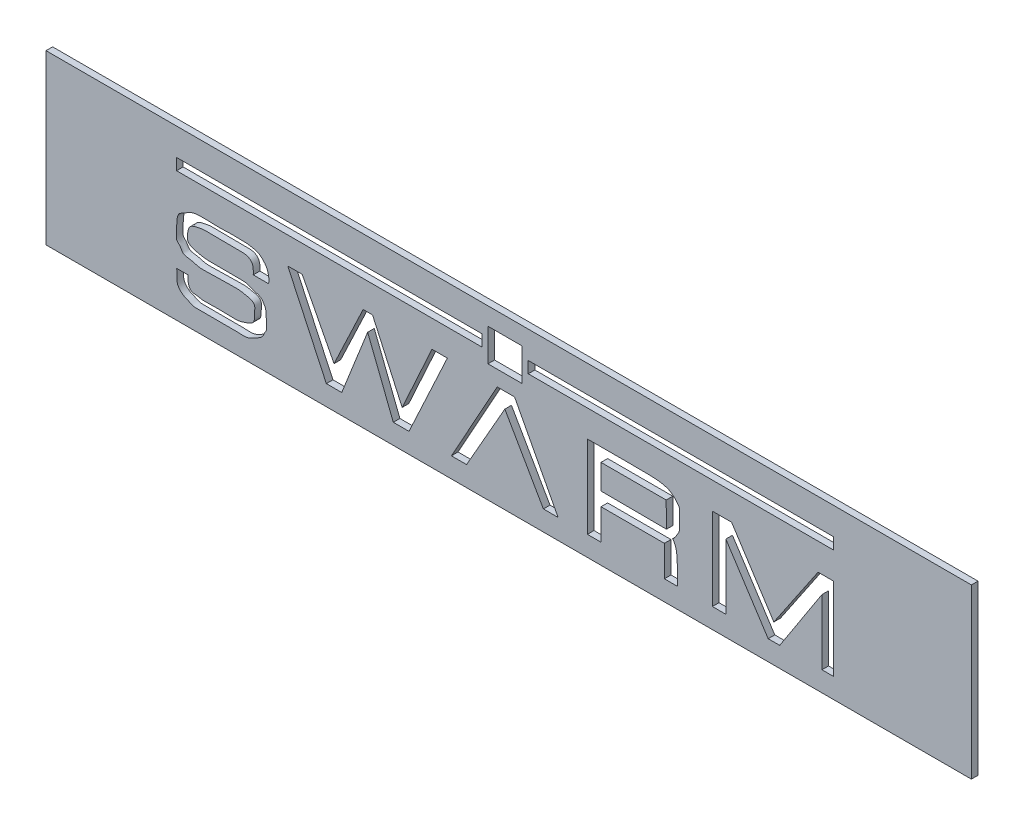
SolidWorks part; units mm, degrees
ref_plane "Front Plane" through (0, 0, 0) normal (0, 0, 1) x (1, 0, 0)
ref_plane "Top Plane" through (0, 0, 0) normal (0, 1, 0) x (1, 0, 0)
ref_plane "Right Plane" through (0, 0, 0) normal (1, 0, 0) x (0, 0, -1)
sketch "Sketch1" plane through (0, 0, 0) normal (0, 0, 1) x (1, 0, 0)
  line L1 (-222.25, -40.4) -> (222.25, -40.4)
  line L2 (-222.25, -40.4) -> (-222.25, 40.4)
  line L3 (-222.25, 40.4) -> (222.25, 40.4)
  line L4 (222.25, -40.4) -> (222.25, 40.4)
  line L5 (-222.25, -40.4) -> (222.25, 40.4) construction
  line L6 (-222.25, 40.4) -> (222.25, -40.4) construction
  point P0 (0, 0)
  dimension "D1" = 80.8
  dimension "D2" = 444.5
sketch "Sketch2" plane through (0, 0, 0) normal (0, 0, 1) x (1, 0, 0)
  line L0 (-115.5, 3.8386) -> (141.8333, 3.8386) construction
  line L1 (148.6027, 8.8845) -> (155.9618, 8.8845)
  line L2 (-222.25, -40.4) -> (222.25, 40.4) construction
  line L3 (-122.7062, -3.1004) -> (-115.2991, -3.1004)
  line L4 (-159.538, -18.7768) -> (-153.9559, -18.7768)
  line L11 (-106.1193, 8.8868) -> (-99.1852, 8.8868)
  line L12 (-99.1852, 8.8868) -> (-83.8919, -20.6337)
  line L13 (-83.8919, -20.6337) -> (-69.9228, 8.8868)
  line L14 (-51.166, -22.4751) -> (-36.8436, 8.8868)
  line L15 (-36.8436, 8.8868) -> (-29.4635, 8.8868)
  line L16 (-29.4635, 8.8868) -> (-47.8873, -30.7813)
  line L17 (-47.8873, -30.7813) -> (-55.4212, -30.7813)
  line L18 (-55.4212, -30.7813) -> (-67.7538, 0.5106)
  line L19 (-67.7538, 0.5106) -> (-80.2018, -30.7813)
  line L20 (-80.2018, -30.7813) -> (-87.5964, -30.7813)
  line L21 (-87.5964, -30.7813) -> (-106.1193, 8.8868)
  line L22 (-5.5054, 8.8868) -> (2.8245, 8.8868)
  line L23 (2.8245, 8.8868) -> (23.7297, -30.7813)
  line L24 (-69.9228, 8.8868) -> (-65.4074, 8.8868)
  line L25 (23.7297, -30.7813) -> (16.6559, -30.7813)
  line L26 (16.6559, -30.7813) -> (-1.8482, 1.5067)
  line L27 (-1.8482, 1.5067) -> (-20.2384, -30.7813)
  line L28 (-20.2384, -30.7813) -> (-27.5191, -30.7813)
  line L29 (-27.5191, -30.7813) -> (-5.5054, 8.8868)
  line L31 (81.1775, -30.7813) -> (74.7806, -30.7813)
  line L32 (74.7806, -30.7813) -> (74.7806, -16.0211)
  line L33 (74.7806, -16.0211) -> (44.3376, -16.0211)
  line L34 (44.3376, -16.0211) -> (44.3376, -30.7813)
  line L35 (44.3376, -30.7813) -> (37.8018, -30.7813)
  line L36 (37.8018, -30.7813) -> (37.8018, 8.8868)
  line L37 (44.3376, 2.4292) -> (75.6394, 2.4292)
  line L38 (75.6394, 2.4292) -> (75.7843, -9.672)
  line L39 (75.7843, -9.672) -> (44.3376, -9.503)
  line L40 (44.3376, -9.503) -> (44.3376, 2.4292)
  line L41 (97.8434, 8.8868) -> (107.0686, 8.8868)
  line L42 (107.0686, 8.8868) -> (127.3507, -22.4751)
  line L43 (155.9618, 8.8845) -> (155.9618, -30.7813)
  line L44 (155.9618, -30.7813) -> (150.4684, -30.7813)
  line L45 (150.4684, -30.7813) -> (150.4684, 0.5106)
  line L46 (150.4684, 0.5106) -> (130.1759, -30.7813)
  line L47 (104.301, 0.5106) -> (124.6363, -30.7813)
  line L48 (104.301, 0.5106) -> (104.301, -30.7813)
  line L49 (104.301, -30.7813) -> (97.8434, -30.7813)
  line L50 (97.8434, -30.7813) -> (97.8434, 8.8868)
  line L51 (-9.9691, 31.9002) -> (6.4727, 31.9002)
  line L52 (6.4727, 31.9002) -> (6.4727, 16.2669)
  line L53 (6.4727, 16.2669) -> (-9.9691, 16.2669)
  line L54 (-9.9691, 16.2669) -> (-9.9691, 31.9002)
  line L55 (-159.538, 27.3371) -> (-12.8583, 27.3371)
  line L56 (-12.8583, 27.3371) -> (-12.8583, 21.802)
  line L57 (-12.8583, 21.802) -> (-159.538, 21.802)
  line L58 (-159.538, 21.802) -> (-159.538, 27.3371)
  line L59 (9.3917, 27.3371) -> (155.9618, 27.3371)
  line L60 (155.9618, 27.3371) -> (155.9618, 21.802)
  line L61 (155.9618, 21.802) -> (9.3917, 21.802)
  line L62 (9.3917, 21.802) -> (9.3917, 27.3371)
  line L63 (124.6363, -30.7813) -> (130.1759, -30.7813)
  line L64 (127.3507, -22.4751) -> (148.6027, 8.8845)
  line L67 (-65.4074, 8.8868) -> (-51.166, -22.4751)
  spline S0 degree 3 poles (-159.538, -18.7768) (-158.9254, -20.7604) (-160.0338, -24.0067) (-158.0752, -26.8721) (-156.7827, -28.0285) (-155.3542, -28.9608) (-153.6112, -29.4504) (-151.687, -30.7531) (-149.0282, -30.5656) (-146.2488, -30.6388) (-143.4961, -30.5846) (-140.3575, -30.6802) (-137.0635, -30.5774) (-133.5732, -30.7552) (-129.7645, -30.523) (-126.0263, -31.1036) (-123.0954, -29.6567) (-121.0482, -28.6069) (-119.5129, -27.5476) (-117.9806, -26.4963) (-117.5945, -24.7711) (-116.2178, -23.2369) (-116.2729, -21.0512) (-116.4273, -18.9158) (-116.5145, -16.7279) (-116.5335, -14.3629) (-117.6265, -12.5487) (-118.7413, -10.752) (-120.8841, -9.8893) (-123.3213, -8.989) (-126.1285, -8.0284) (-129.1797, -7.9818) (-132.6567, -7.9437) (-136.1662, -7.9641) (-139.6914, -7.8481) (-142.7038, -7.977) (-145.7462, -7.8977) (-149.02, -7.3404) (-151.7998, -6.6205) (-154.3739, -5.1513) (-154.4169, -2.1422) (-153.9842, 0.0177) (-153.3229, 1.4929) (-152.1841, 2.6194) (-149.724, 3.2151) (-147.0515, 3.8096) (-144.5149, 3.8293) (-142.0882, 3.798) (-139.4048, 3.6293) (-136.0192, 3.7204) (-132.4223, 4.025) (-129.0004, 3.7944) (-126.0345, 3.6179) (-122.4792, 1.9389) (-122.6279, -1.5087) (-122.7062, -3.1004) knots 0 0 0 0 0.045054 0.057588 0.06928 0.080802 0.092277 0.106354 0.127202 0.144645 0.164213 0.183717 0.209335 0.232061 0.255492 0.288322 0.306622 0.321383 0.335716 0.345441 0.358195 0.37015 0.38632 0.400449 0.414879 0.431506 0.447942 0.457663 0.474286 0.493165 0.512086 0.534672 0.555463 0.583849 0.606894 0.628074 0.645915 0.669488 0.696094 0.705592 0.727557 0.749037 0.752567 0.760627 0.780862 0.803042 0.817274 0.832853 0.853078 0.872585 0.902546 0.927349 0.942853 0.96434 1 1 1 1
  spline S1 degree 3 poles (-153.9559, -18.7768) (-154.2853, -20.0497) (-153.9987, -25.3376) (-149.6795, -25.0443) (-147.1215, -25.938) (-144.2062, -25.5842) (-141.1377, -25.7328) (-137.6762, -25.5563) (-133.5792, -25.7617) (-129.7458, -25.9711) (-126.6037, -24.8852) (-124.4522, -24.2019) (-122.3335, -22.8729) (-121.9937, -20.2176) (-122.0749, -17.8342) (-121.8324, -15.5926) (-123.3502, -13.8155) (-125.9135, -13.4487) (-129.8454, -12.443) (-133.9826, -12.8819) (-138.2569, -12.8117) (-141.6373, -12.8069) (-145.0401, -12.8841) (-148.8398, -13.1942) (-152.3535, -11.6551) (-156.6863, -11.6717) (-157.6101, -8.5799) (-159.708, -7.277) (-159.5074, -4.5714) (-159.6356, -2.0717) (-159.3386, 0.5626) (-159.2492, 2.8233) (-158.4453, 4.6869) (-157.1747, 5.31) (-155.6278, 6.0415) (-153.4818, 7.7805) (-149.8068, 8.7008) (-146.1857, 8.6827) (-142.9258, 8.5048) (-139.4403, 8.4212) (-135.9096, 8.3715) (-132.1356, 8.7115) (-128.7544, 8.5836) (-125.0497, 8.4839) (-121.9732, 7.8854) (-119.5509, 6.9289) (-118.3925, 5.8138) (-115.7205, 3.2206) (-114.8607, -0.3531) (-115.2991, -3.1004) knots 0 0 0 0 0.044 0.060874 0.079385 0.099252 0.119243 0.142092 0.169518 0.203051 0.218676 0.236484 0.249692 0.266333 0.286428 0.300449 0.309198 0.330906 0.350445 0.392283 0.413701 0.437672 0.460875 0.483404 0.513308 0.540183 0.558429 0.571897 0.586029 0.608414 0.624677 0.639266 0.655062 0.662122 0.667468 0.689978 0.717351 0.742329 0.763638 0.783749 0.813269 0.835402 0.860711 0.882041 0.910691 0.924247 0.934075 0.943084 1 1 1 1
  spline S2 degree 3 poles (78.7325, -12.1243) (80.2175, -13.9645) (80.8639, -17.0237) (80.928, -21.2717) (81.2113, -25.3568) (81.1489, -28.6738) (81.1775, -30.7813) knots 0 0 0 0 0.356856 0.478923 0.668595 1 1 1 1
  spline S3 degree 3 poles (37.8018, 8.8868) (46.202, 8.7772) (56.3558, 8.9982) (68.9426, 8.8085) (74.1648, 8.5004) (77.7762, 7.0094) (79.1056, 5.7569) (80.1469, 5.0761) (80.8071, 3.8559) (81.9789, 2.8637) (82.2399, 0.5694) (82.0396, -1.959) (82.1233, -4.9864) (82.1121, -7.6192) (80.4647, -9.9144) (79.7992, -11.4971) (78.7325, -12.1243) knots 0 0 0 0 0.407287 0.490761 0.61039 0.65871 0.674575 0.698789 0.717498 0.740771 0.770154 0.822864 0.865361 0.917919 0.943853 1 1 1 1
  point P10 (0, 0)
  point P20 (0, 0)
  point P72 (0, 0)
  point P76 (0, 0)
  point P79 (0, 0)
  point P83 (82.0013, -4.8044)
  point P87 (82.1051, -4.8044)
  point P91 (0, 0)
  point P96 (0, 0)
  point P99 (82.0866, -2.172)
  point P105 (82.1392, 1.0929)
  point P113 (78.6792, -12.1243)
extrude "Boss-Extrude4" add sketch "Sketch1" against normal blind 3.175
extrude "Cut-Extrude1" cut sketch "Sketch2" against normal blind 16.51
